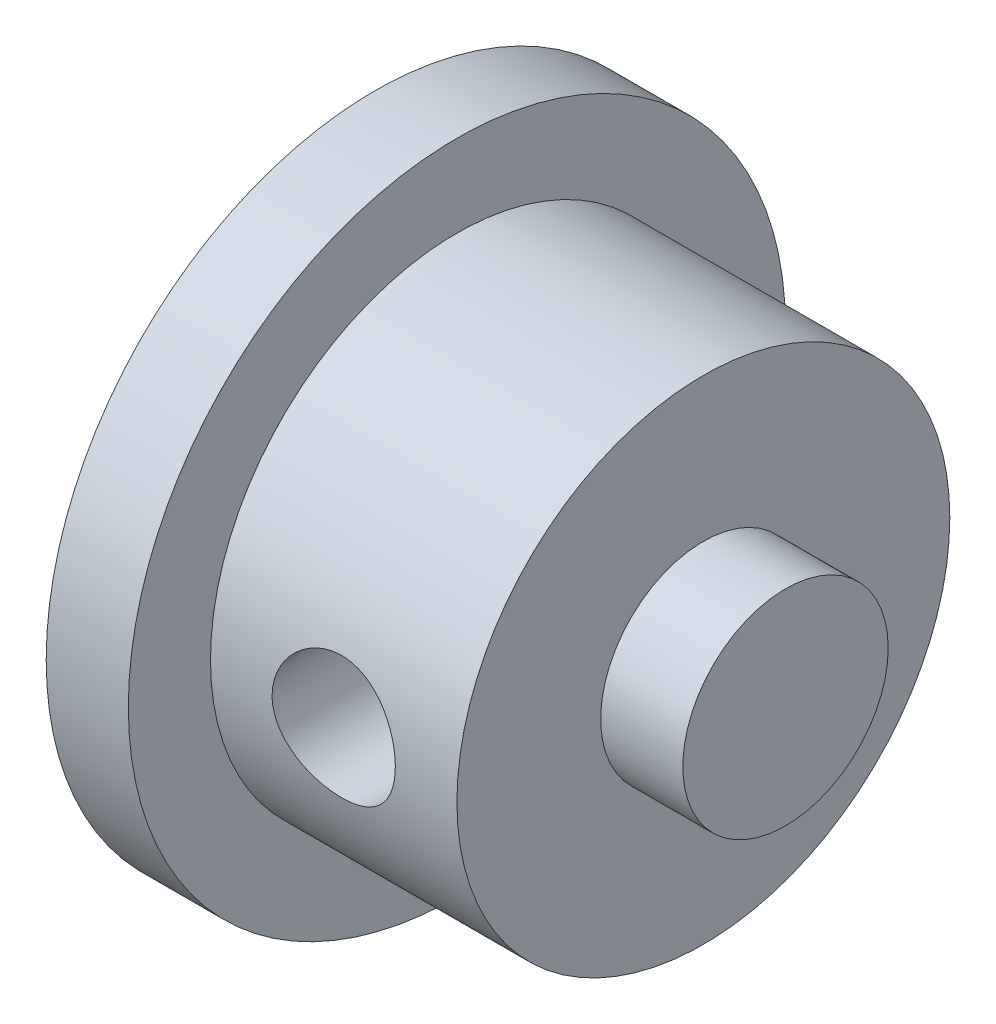
SolidWorks part; units mm, degrees
ref_plane "Front Plane" through (0, 0, 0) normal (0, 0, 1) x (1, 0, 0)
ref_plane "Top Plane" through (0, 0, 0) normal (0, 1, 0) x (1, 0, 0)
ref_plane "Right Plane" through (0, 0, 0) normal (1, 0, 0) x (0, 0, -1)
sketch "Sketch1" plane through (0, 0, 0) normal (0, 0, 1) x (1, 0, 0)
  line L20 (-85.1361, -10.256) -> (-85.1361, -18.256)
  line L21 (-85.1361, -18.256) -> (-75.1361, -18.256)
  line L22 (-75.1361, -18.256) -> (-75.1361, -10.256)
  line L23 (-75.1361, -10.256) -> (-77.1361, -10.256)
  line L24 (-77.1361, -10.256) -> (-77.1361, -12.256)
  line L25 (-77.1361, -12.256) -> (-83.1361, -12.256)
  line L26 (-83.1361, -12.256) -> (-83.1361, -10.256)
  line L27 (-83.1361, -10.256) -> (-85.1361, -10.256)
  dimension "D1" = 6
  dimension "D2" = 2
  dimension "D3" = 6
  dimension "D4" = 8
revolve "Revolve2" add sketch "Sketch1" angle 360 about L21
sketch "Sketch2" plane through (-75.1361, 0, 0) normal (1, 0, 0) x (0, 0, -1)
  circle A0 centre (0, -18.256) radius 2.5
  circle A2 centre (0, -18.256) radius 8 construction
  dimension "D1" = 5
ref_plane "Plane1" through (0, 0, 0) normal (0, 0, 1) x (1, 0, 0)
sketch "Sketch5" plane through (0, 0, 0) normal (0, 0, 1) x (1, 0, 0)
  line L1 (-85.1361, -10.256) -> (-85.1361, -26.256) construction
  line L2 (-83.1361, -24.256) -> (-77.1361, -24.256) construction
  circle A0 centre (-80.1361, -18.256) radius 1.5
  dimension "D2" = 3
  dimension "D1" = 5
  dimension "D3" = 6
extrude "Cut-Extrude2" cut sketch "Sketch5" against normal through all both and the other way through all
sketch "Sketch7" plane through (-75.1361, 0, 0) normal (1, 0, 0) x (0, 0, -1)
  circle A0 centre (0, -18.256) radius 8
extrude "Cut-Extrude3" cut sketch "Sketch7" against normal blind 2
extrude "Boss-Extrude1" add sketch "Sketch2" along normal blind 2 from surface at -2 starting at face at (-77.1361, -18.256, -6)
